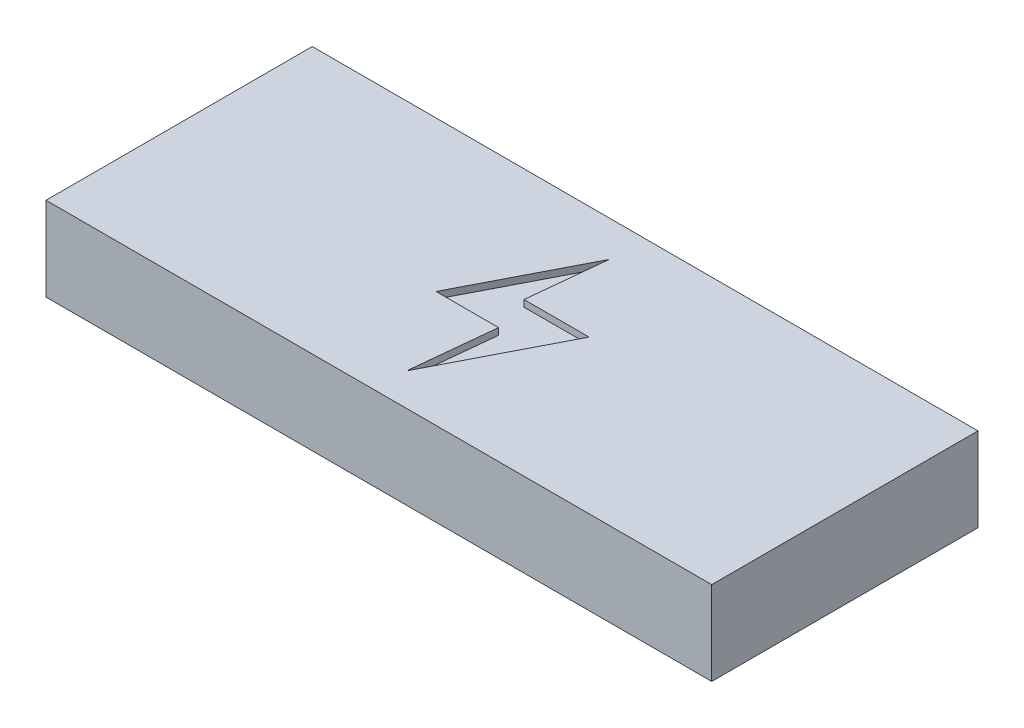
SolidWorks part; units mm, degrees
ref_plane "Front Plane" through (0, 0, 0) normal (0, 0, 1) x (1, 0, 0)
ref_plane "Top Plane" through (0, 0, 0) normal (0, 1, 0) x (1, 0, 0)
ref_plane "Right Plane" through (0, 0, 0) normal (1, 0, 0) x (0, 0, -1)
sketch "Sketch1" plane through (0, 0, 0) normal (0, 1, 0) x (1, 0, 0)
  line L1 (-25, -10) -> (25, -10)
  line L2 (-25, -10) -> (-25, 10)
  line L3 (-25, 10) -> (25, 10)
  line L4 (25, -10) -> (25, 10)
  line L5 (-25, -10) -> (25, 10) construction
  line L6 (-25, 10) -> (25, -10) construction
  point P0 (0, 0)
  dimension "D1" = 50
  dimension "D2" = 20
extrude "Boss-Extrude1" add sketch "Sketch1" along normal blind 6.3
sketch "Sketch2" plane through (0, 6.3, 0) normal (0, 1, 0) x (1, 0, 0)
  line L0 (0, 7.306) -> (-4.4203, -1.2847)
  line L1 (-4.4203, -1.2847) -> (0.2782, -1.2847)
  line L2 (0.2782, -1.2847) -> (-0.3621, -7.5503)
  line L3 (-0.3621, -7.5503) -> (4.293, 1.4968)
  line L4 (4.293, 1.4968) -> (-0.5937, 1.4968)
  line L5 (-0.5937, 1.4968) -> (0, 7.306)
  point P5 (0, 0)
  point P7 (-0.6815, 0.6373)
extrude "Cut-Extrude1" cut sketch "Sketch2" against normal blind 0.5
